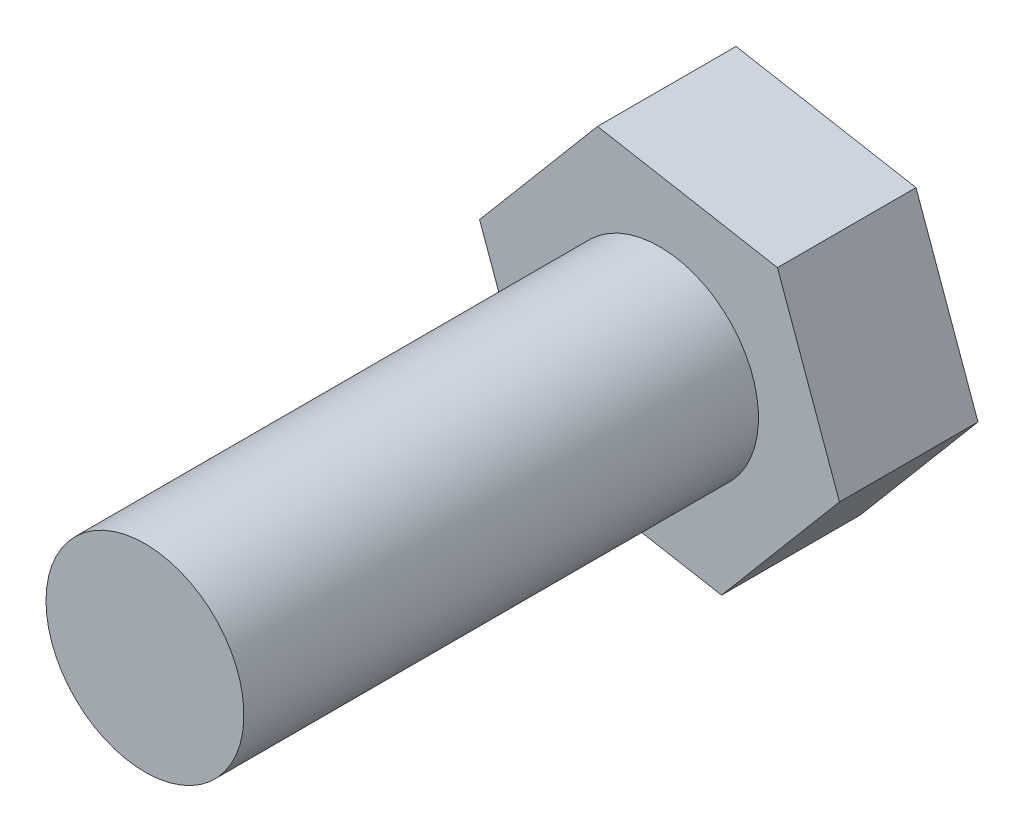
SolidWorks part; units mm, degrees
ref_plane "正面" through (0, 0, 0) normal (0, 0, 1) x (1, 0, 0)
ref_plane "平面" through (0, 0, 0) normal (0, 1, 0) x (1, 0, 0)
ref_plane "右側面" through (0, 0, 0) normal (1, 0, 0) x (0, 0, -1)
sketch "ｽｹｯﾁ1" plane through (0, 0, 0) normal (0, 0, 1) x (1, 0, 0)
  line L1 (-2.9798, -3.529) -> (1.5663, -4.3451)
  line L2 (1.5663, -4.3451) -> (4.5461, -0.8161)
  line L3 (4.5461, -0.8161) -> (2.9798, 3.529)
  line L4 (2.9798, 3.529) -> (-1.5663, 4.3451)
  line L5 (-1.5663, 4.3451) -> (-4.5461, 0.8161)
  line L6 (-4.5461, 0.8161) -> (-2.9798, -3.529)
  circle A0 centre (0, 0) radius 4 construction
  dimension "D1" = 8
extrude "ﾎﾞｽ - 押し出し1" add sketch "ｽｹｯﾁ1" along normal blind 3.5
sketch "ｽｹｯﾁ2" plane through (0, 0, 3.5) normal (0, 0, 1) x (1, 0, 0)
  circle A0 centre (0, 0) radius 2.5
  dimension "D1" = 5
extrude "ﾎﾞｽ - 押し出し2" add sketch "ｽｹｯﾁ2" along normal blind 13
cosmetic thread "ねじ山1" parameters "D2"=3
